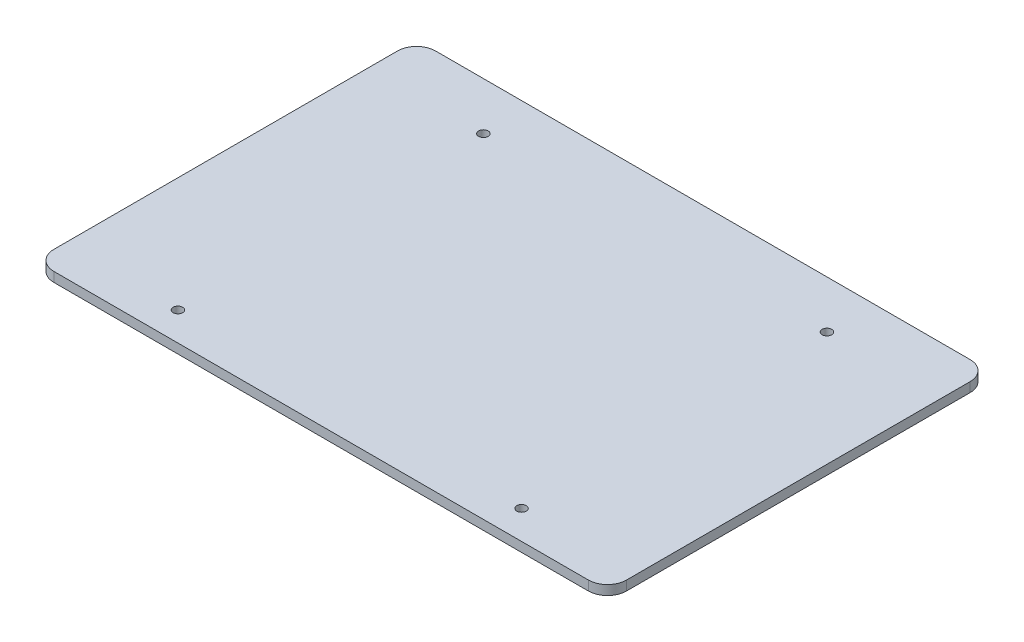
SolidWorks part; units mm, degrees
ref_plane "Front Plane" through (0, 0, 0) normal (0, 0, 1) x (1, 0, 0)
ref_plane "Top Plane" through (0, 0, 0) normal (0, 1, 0) x (1, 0, 0)
ref_plane "Right Plane" through (0, 0, 0) normal (1, 0, 0) x (0, 0, -1)
sketch "Sketch1" plane through (0, 0, 0) normal (0, 1, 0) x (1, 0, 0)
  line L0 (0, 0) -> (0, 133.3169) construction
  line L1 (-140, -100) -> (140, -100)
  line L2 (-150, -90) -> (-150, 90)
  line L3 (-140, 100) -> (140, 100)
  line L4 (150, -90) -> (150, 90)
  line L5 (-150, -100) -> (150, 100) construction
  line L6 (-150, 100) -> (150, -100) construction
  arc A0 (150, -90) -> (140, -100) centre (140, -90) cw
  arc A1 (140, 100) -> (150, 90) centre (140, 90) cw
  arc A2 (-140, -100) -> (-150, -90) centre (-140, -90) cw
  arc A3 (-140, 100) -> (-150, 90) centre (-140, 90) ccw
  circle A4 centre (-90, -85) radius 2.5
  circle A5 centre (90, -85) radius 2.5
  circle A6 centre (90, 75) radius 2.5
  circle A7 centre (-90, 75) radius 2.5
  point P0 (0, 0)
  dimension "D3" = 10
  dimension "D4" = 5
  dimension "D5" = 90
  dimension "D7" = 90
  dimension "D8" = 90
  dimension "D9" = 160
  dimension "D11" = 15
  dimension "D12" = 15
  dimension "D1" = 200
  dimension "D2" = 300
  dimension "D6" = 90
  dimension "D10" = 160
extrude "Boss-Extrude2" add sketch "Sketch1" along normal blind 5
